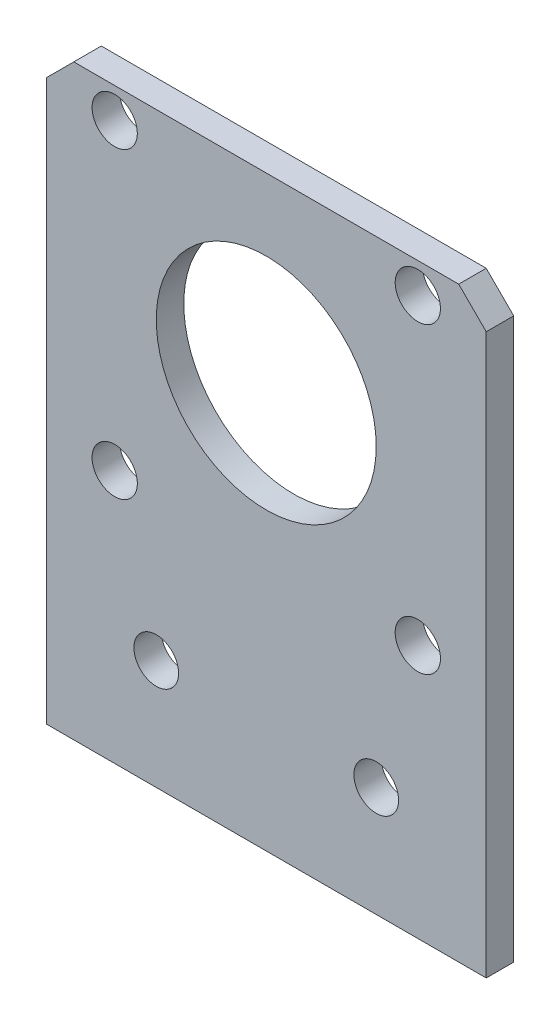
SolidWorks part; units mm, degrees
ref_plane "Front Plane" through (0, 0, 0) normal (0, 0, 1) x (1, 0, 0)
ref_plane "Top Plane" through (0, 0, 0) normal (0, 1, 0) x (1, 0, 0)
ref_plane "Right Plane" through (0, 0, 0) normal (1, 0, 0) x (0, 0, -1)
sketch "Sketch1" plane through (0, 0, 0) normal (0, 0, 1) x (1, 0, 0)
  line L0 (-50.8, 12.7) -> (0, 12.7) construction
  line L1 (0, 0) -> (-50.8, 0)
  line L2 (0, 0) -> (0, 67.8)
  line L3 (0, 67.8) -> (-50.8, 67.8)
  line L4 (-50.8, 0) -> (-50.8, 67.8)
  line L5 (-25.4, 0) -> (-25.4, 67.8) construction
  line L6 (-50.8, 25.4) -> (0, 25.4) construction
  line L7 (-42.9, 46.8) -> (-7.9, 46.8) construction
  line L8 (-7.9, 29.3) -> (-42.9, 29.3) construction
  line L9 (-7.9, 29.3) -> (-7.9, 64.3) construction
  line L10 (-7.9, 64.3) -> (-42.9, 64.3) construction
  line L11 (-42.9, 29.3) -> (-42.9, 64.3) construction
  line L12 (-7.9, 29.3) -> (-42.9, 64.3) construction
  line L13 (-7.9, 64.3) -> (-42.9, 29.3) construction
  circle A0 centre (-38.1, 12.7) radius 2.5813
  circle A1 centre (-12.7, 12.7) radius 2.5813
  circle A2 centre (-25.4, 46.8) radius 12.7
  circle A3 centre (-42.9, 64.3) radius 2.613
  circle A4 centre (-7.9, 64.3) radius 2.613
  circle A5 centre (-7.9, 29.3) radius 2.613
  circle A6 centre (-42.9, 29.3) radius 2.613
  dimension "D4" = 12.7
  dimension "D5" = 5.1625
  dimension "D7" = 25.4
  dimension "D11" = 5.226
  dimension "D1" = 50.8
  dimension "D2" = 42.4
  dimension "D3" = 12.7
  dimension "D6" = 12.7
  dimension "D8" = 21
  dimension "D9" = 35
  dimension "D10" = 35
extrude "Boss-Extrude1" add sketch "Sketch1" along normal blind 3.175
chamfer "Chamfer1" distance 3.175 angle 45 2 edges at (0, 67.8, 1.5875) (-50.8, 67.8, 1.5875)
